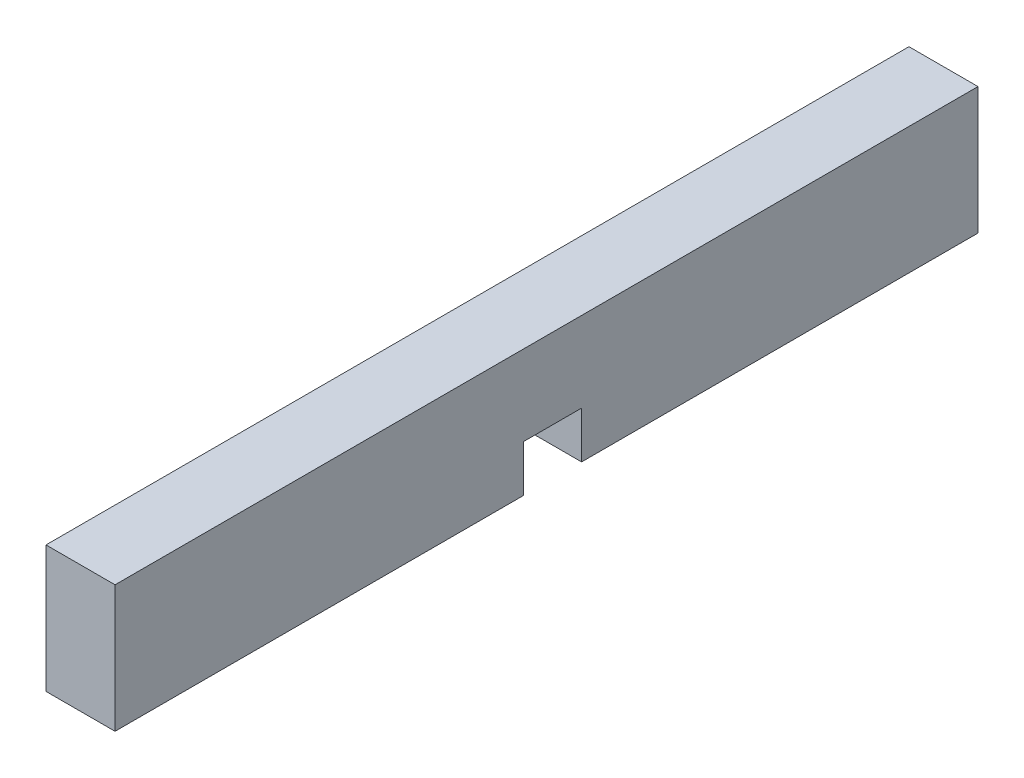
SolidWorks part; units mm, degrees
ref_plane "Front Plane" through (0, 0, 0) normal (0, 0, 1) x (1, 0, 0)
ref_plane "Top Plane" through (0, 0, 0) normal (0, 1, 0) x (1, 0, 0)
ref_plane "Right Plane" through (0, 0, 0) normal (1, 0, 0) x (0, 0, -1)
sketch "Sketch1" plane through (0, 0, 0) normal (1, 0, 0) x (0, 0, -1)
  line L1 (-29.3624, 4.318) -> (29.3624, 4.318)
  line L2 (-29.3624, 4.318) -> (-29.3624, -4.318)
  line L3 (-29.3624, -4.318) -> (29.3624, -4.318)
  line L4 (29.3624, 4.318) -> (29.3624, -4.318)
  line L5 (-29.3624, 4.318) -> (29.3624, -4.318) construction
  line L6 (-29.3624, -4.318) -> (29.3624, 4.318) construction
  point P0 (0, 0)
  dimension "D1" = 58.7248
  dimension "D2" = 8.636
extrude "Boss-Extrude1" add sketch "Sketch1" along normal mid plane 4.699
sketch "Sketch2" plane through (2.3495, 0, 0) normal (1, 0, 0) x (0, 0, -1)
  line L0 (-29.3624, -4.318) -> (29.3624, -4.318) construction
  line L1 (-1.5748, -4.318) -> (2.3876, -4.318)
  line L2 (-1.5748, -4.318) -> (-1.5748, -1.143)
  line L3 (-1.5748, -1.143) -> (2.3876, -1.143)
  line L4 (2.3876, -4.318) -> (2.3876, -1.143)
  line L5 (-29.3624, 4.318) -> (-29.3624, -4.318) construction
  point P6 (3.3934, 1.0689)
  dimension "D1" = 27.7876
  dimension "D2" = 3.9624
  dimension "D3" = 3.175
extrude "Cut-Extrude1" cut sketch "Sketch2" against normal through all and the other way through all
